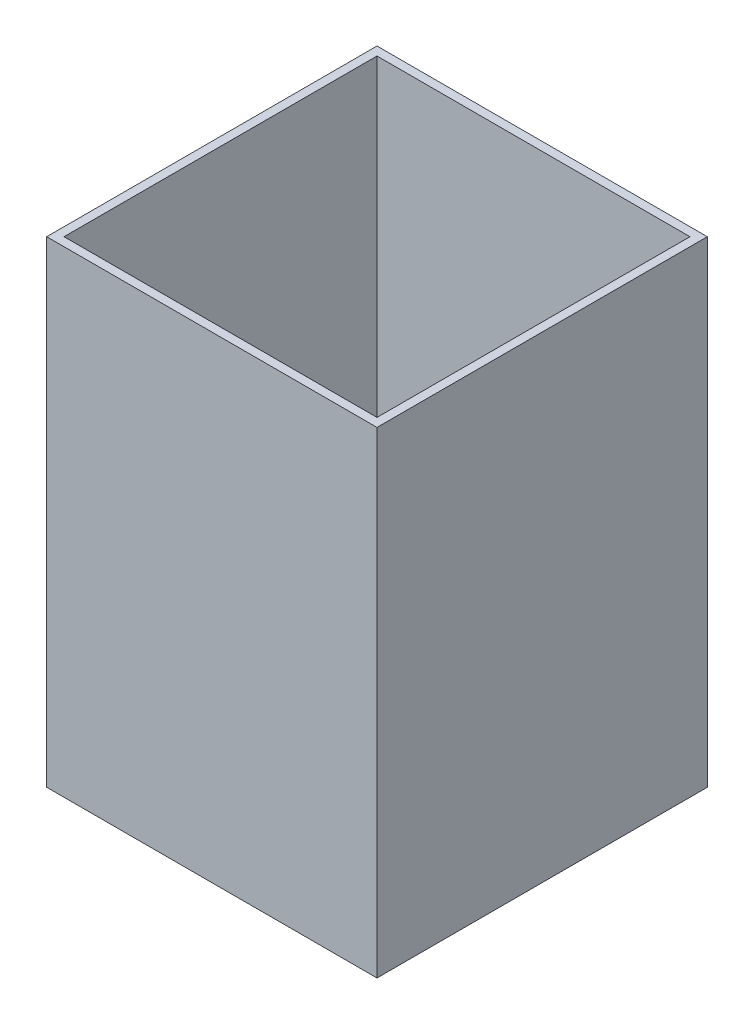
SolidWorks part; units mm, degrees
ref_plane "Front Plane" through (0, 0, 0) normal (0, 0, 1) x (1, 0, 0)
ref_plane "Top Plane" through (0, 0, 0) normal (0, 1, 0) x (1, 0, 0)
ref_plane "Right Plane" through (0, 0, 0) normal (1, 0, 0) x (0, 0, -1)
sketch "Sketch1" plane through (0, 0, 0) normal (0, 1, 0) x (1, 0, 0)
  line L0 (2, 74.2) -> (74.2, 74.2)
  line L1 (0, 0) -> (76.2, 0)
  line L2 (0, 0) -> (0, 76.2)
  line L3 (0, 76.2) -> (76.2, 76.2)
  line L4 (76.2, 0) -> (76.2, 76.2)
  line L5 (74.2, 2) -> (74.2, 74.2)
  line L6 (2, 2) -> (74.2, 2)
  line L7 (2, 2) -> (2, 74.2)
  dimension "D1" = 76.2
  dimension "D2" = 76.2
  dimension "D3" = 2
extrude "Boss-Extrude1" add sketch "Sketch1" along normal blind 110
